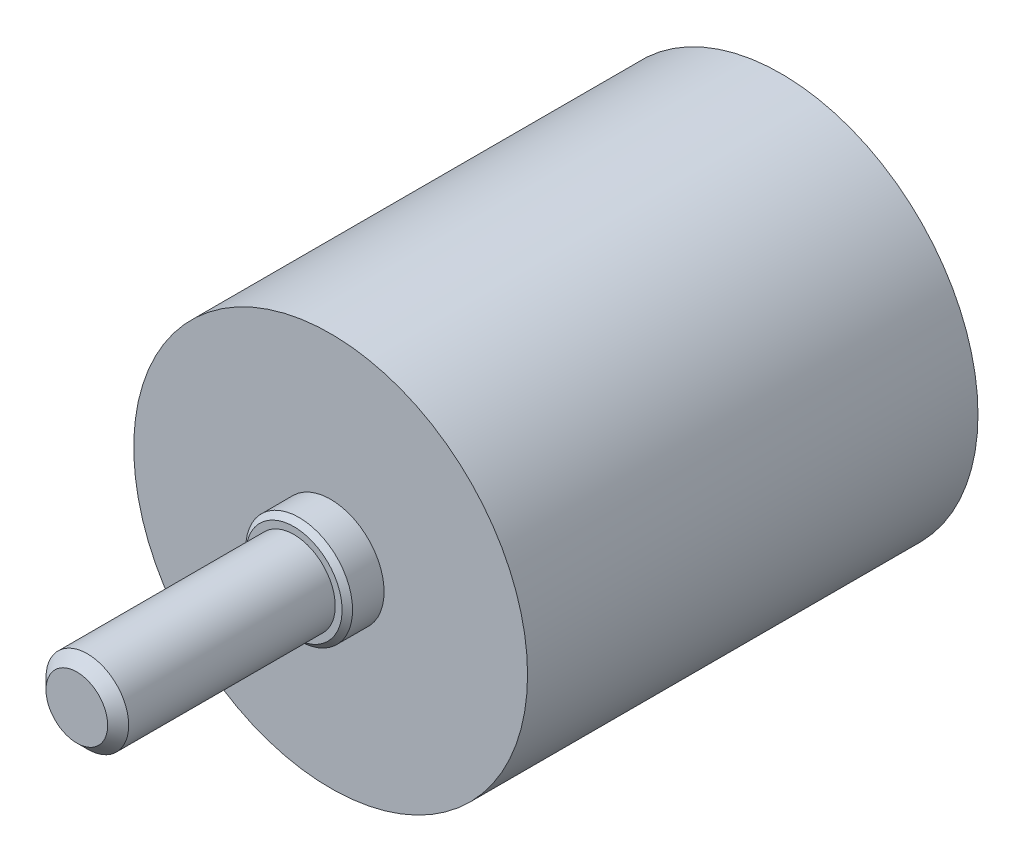
SolidWorks part; units mm, degrees
ref_plane "Front Plane" through (0, 0, 0) normal (0, 0, 1) x (1, 0, 0)
ref_plane "Top Plane" through (0, 0, 0) normal (0, 1, 0) x (1, 0, 0)
ref_plane "Right Plane" through (0, 0, 0) normal (1, 0, 0) x (0, 0, -1)
sketch "Sketch1" plane through (0, 0, 0) normal (1, 0, 0) x (0, 0, -1)
  line L0 (0, 0) -> (0, 4)
  line L1 (0, 4) -> (21, 4)
  line L2 (21, 4) -> (21, 5.1689)
  line L3 (21, 5.1689) -> (24.556, 5.1689)
  line L4 (24.556, 5.1689) -> (24.556, 19.05)
  line L5 (24.556, 19.05) -> (68.1347, 19.05)
  line L6 (68.1347, 19.05) -> (68.1347, 5.1689)
  line L7 (68.1347, 5.1689) -> (72.7964, 5.1689)
  line L8 (72.7964, 5.1689) -> (72.7964, 0)
  line L9 (0, 0) -> (72.7964, 0) construction
  line L10 (0, 0) -> (72.7964, 0)
  point P3 (70.4656, 5.1689)
  dimension "D1" = 8
  dimension "D2" = 38.1
  dimension "D3" = 21
  dimension "D4" = 3.556
  dimension "D5" = 10.3378
  dimension "D6" = 10.3378
  dimension "D7" = 72.7964
revolve "Revolve1" add sketch "Sketch1" angle 360 about L9
chamfer "Chamfer1" distance 1.016 angle 45 1 edges at (4, 0, 0)
chamfer "Chamfer2" distance 0.508 angle 45 2 edges at (5.1689, 0, -21) (5.1689, 0, -72.7964)
